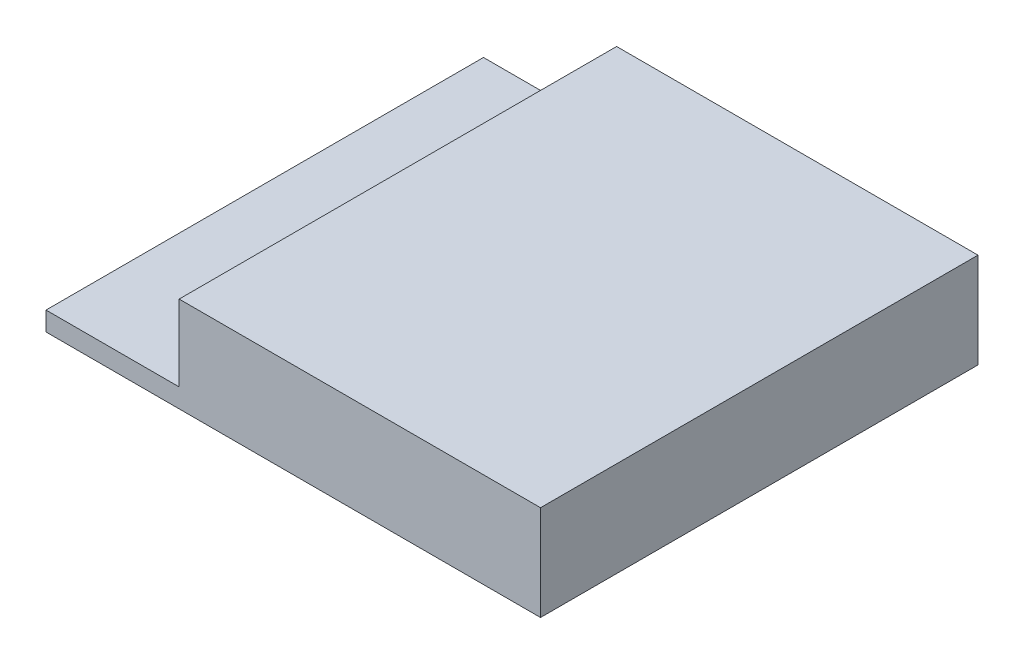
SolidWorks part; units mm, degrees
ref_plane "Front Plane" through (0, 0, 0) normal (0, 0, 1) x (1, 0, 0)
ref_plane "Top Plane" through (0, 0, 0) normal (0, 1, 0) x (1, 0, 0)
ref_plane "Right Plane" through (0, 0, 0) normal (1, 0, 0) x (0, 0, -1)
sketch "Sketch1" plane through (0, 0, 0) normal (0, 1, 0) x (1, 0, 0)
  line L1 (-14.802, -33.3614) -> (11.198, -33.3614)
  line L2 (-14.802, -33.3614) -> (-14.802, -10.3614)
  line L3 (-14.802, -10.3614) -> (11.198, -10.3614)
  line L4 (11.198, -33.3614) -> (11.198, -10.3614)
  dimension "D1" = 23
  dimension "D2" = 26
extrude "Boss-Extrude1" add sketch "Sketch1" along normal blind 5
sketch "Sketch2" plane through (0, 5, 0) normal (0, 1, 0) x (1, 0, 0)
  line L0 (-14.802, -33.3614) -> (11.198, -33.3614) construction
  line L1 (-14.802, -10.3614) -> (-7.802, -10.3614)
  line L2 (-14.802, -10.3614) -> (-14.802, -33.3614)
  line L3 (-14.802, -33.3614) -> (-7.802, -33.3614)
  line L4 (-7.802, -10.3614) -> (-7.802, -33.3614)
  dimension "D1" = 7
extrude "Cut-Extrude1" cut sketch "Sketch2" against normal offset from surface (4 mm away) 1 up to face at (-1.802, 0, 21.8614)
